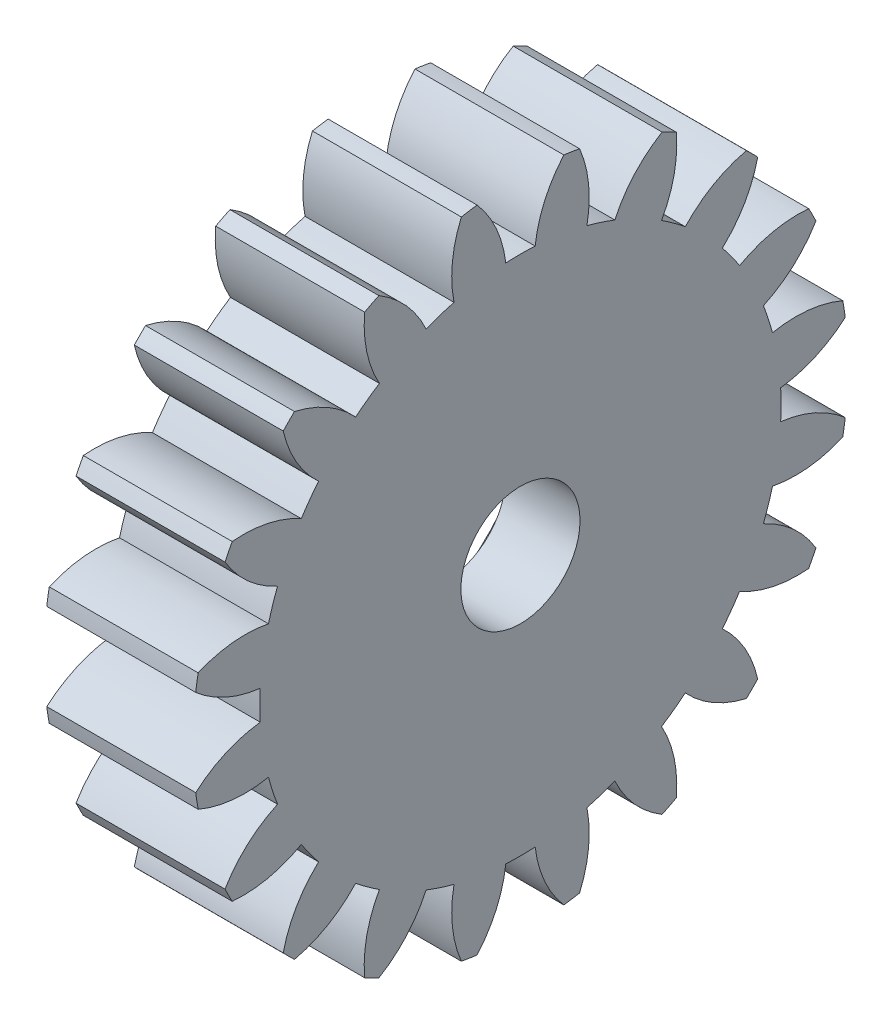
SolidWorks part; units mm, degrees
ref_plane "Front Plane" through (0, 0, 0) normal (0, 0, 1) x (1, 0, 0)
ref_plane "Top Plane" through (0, 0, 0) normal (0, 1, 0) x (1, 0, 0)
ref_plane "Right Plane" through (0, 0, 0) normal (1, 0, 0) x (0, 0, -1)
ref_plane "Plane1" through (-18.1667, 0, 0) normal (1, 0, 0) x (0, 0, -1)
sketch "Sketch1" plane through (-18.1667, 0, 0) normal (1, 0, 0) x (0, 0, -1)
  circle A0 centre (-10.2644, 2.8855) radius 11
  arc A1 (-32.0707, 5.7982) -> (-27.7356, 3.8717) centre (-26.8004, 11.8169) ccw
  arc A2 (-27.7356, 3.8717) -> (-27.7356, 1.8994) centre (-10.2644, 2.8855) ccw
  arc A3 (-27.7356, 1.8994) -> (-32.0707, -0.0272) centre (-26.8004, -6.0458) ccw
  arc A4 (-32.0707, -0.0272) -> (-31.9035, -1.0829) centre (-10.2644, 2.8855) ccw
  arc A5 (-31.9035, -1.0829) -> (-27.1852, -1.5755) centre (-28.751, 6.2698) ccw
  arc A6 (-27.1852, -1.5755) -> (-26.5757, -3.4513) centre (-10.2644, 2.8855) ccw
  arc A7 (-26.5757, -3.4513) -> (-30.1033, -6.6231) centre (-23.2311, -10.7186) ccw
  arc A8 (-30.1033, -6.6231) -> (-29.6181, -7.5755) centre (-10.2644, 2.8855) ccw
  arc A9 (-29.6181, -7.5755) -> (-24.9785, -6.586) centre (-28.892, 0.3915) ccw
  arc A10 (-24.9785, -6.586) -> (-23.8192, -8.1816) centre (-10.2644, 2.8855) ccw
  arc A11 (-23.8192, -8.1816) -> (-26.194, -12.2883) centre (-18.3926, -14.0597) ccw
  arc A12 (-26.194, -12.2883) -> (-25.4382, -13.0441) centre (-10.2644, 2.8855) ccw
  arc A13 (-25.4382, -13.0441) -> (-21.3315, -10.6693) centre (-27.2096, -5.2427) ccw
  arc A14 (-21.3315, -10.6693) -> (-19.7358, -11.8286) centre (-10.2644, 2.8855) ccw
  arc A15 (-19.7358, -11.8286) -> (-20.7254, -16.4682) centre (-12.7584, -15.7421) ccw
  arc A16 (-20.7254, -16.4682) -> (-19.773, -16.9535) centre (-10.2644, 2.8855) ccw
  arc A17 (-19.773, -16.9535) -> (-16.6012, -13.4258) centre (-23.8685, -10.0812) ccw
  arc A18 (-16.6012, -13.4258) -> (-14.7254, -14.0353) centre (-10.2644, 2.8855) ccw
  arc A19 (-14.7254, -14.0353) -> (-14.2328, -18.7536) centre (-6.8801, -15.6011) ccw
  arc A20 (-14.2328, -18.7536) -> (-13.1771, -18.9208) centre (-10.2644, 2.8855) ccw
  arc A21 (-13.1771, -18.9208) -> (-11.2505, -14.5857) centre (-19.1957, -13.6505) ccw
  arc A22 (-11.2505, -14.5857) -> (-9.2782, -14.5857) centre (-10.2644, 2.8855) ccw
  arc A23 (-9.2782, -14.5857) -> (-7.3517, -18.9208) centre (-1.333, -13.6505) ccw
  arc A24 (-7.3517, -18.9208) -> (-6.296, -18.7536) centre (-10.2644, 2.8855) ccw
  arc A25 (-6.296, -18.7536) -> (-5.8034, -14.0353) centre (-13.6486, -15.6011) ccw
  arc A26 (-5.8034, -14.0353) -> (-3.9276, -13.4258) centre (-10.2644, 2.8855) ccw
  arc A27 (-3.9276, -13.4258) -> (-0.7557, -16.9535) centre (3.3397, -10.0812) ccw
  arc A28 (-0.7557, -16.9535) -> (0.1967, -16.4682) centre (-10.2644, 2.8855) ccw
  arc A29 (0.1967, -16.4682) -> (-0.7929, -11.8286) centre (-7.7703, -15.7421) ccw
  arc A30 (-0.7929, -11.8286) -> (0.8028, -10.6693) centre (-10.2644, 2.8855) ccw
  arc A31 (0.8028, -10.6693) -> (4.9095, -13.0441) centre (6.6809, -5.2427) ccw
  arc A32 (4.9095, -13.0441) -> (5.6653, -12.2883) centre (-10.2644, 2.8855) ccw
  arc A33 (5.6653, -12.2883) -> (3.2905, -8.1816) centre (-2.1361, -14.0597) ccw
  arc A34 (3.2905, -8.1816) -> (4.4498, -6.586) centre (-10.2644, 2.8855) ccw
  arc A35 (4.4498, -6.586) -> (9.0894, -7.5755) centre (8.3633, 0.3915) ccw
  arc A36 (9.0894, -7.5755) -> (9.5746, -6.6231) centre (-10.2644, 2.8855) ccw
  arc A37 (9.5746, -6.6231) -> (6.047, -3.4513) centre (2.7024, -10.7186) ccw
  arc A38 (6.047, -3.4513) -> (6.6565, -1.5755) centre (-10.2644, 2.8855) ccw
  arc A39 (6.6565, -1.5755) -> (11.3748, -1.0829) centre (8.2223, 6.2698) ccw
  arc A40 (11.3748, -1.0829) -> (11.542, -0.0272) centre (-10.2644, 2.8855) ccw
  arc A41 (11.542, -0.0272) -> (7.2068, 1.8994) centre (6.2717, -6.0458) ccw
  arc A42 (7.2068, 1.8994) -> (7.2068, 3.8717) centre (-10.2644, 2.8855) ccw
  arc A43 (7.2068, 3.8717) -> (11.542, 5.7982) centre (6.2717, 11.8169) ccw
  arc A44 (11.542, 5.7982) -> (11.3748, 6.8539) centre (-10.2644, 2.8855) ccw
  arc A45 (11.3748, 6.8539) -> (6.6565, 7.3465) centre (8.2223, -0.4988) ccw
  arc A46 (6.6565, 7.3465) -> (6.047, 9.2223) centre (-10.2644, 2.8855) ccw
  arc A47 (6.047, 9.2223) -> (9.5746, 12.3942) centre (2.7024, 16.4896) ccw
  arc A48 (9.5746, 12.3942) -> (9.0894, 13.3465) centre (-10.2644, 2.8855) ccw
  arc A49 (9.0894, 13.3465) -> (4.4498, 12.357) centre (8.3633, 5.3796) ccw
  arc A50 (4.4498, 12.357) -> (3.2905, 13.9527) centre (-10.2644, 2.8855) ccw
  arc A51 (3.2905, 13.9527) -> (5.6653, 18.0594) centre (-2.1361, 19.8308) ccw
  arc A52 (5.6653, 18.0594) -> (4.9095, 18.8152) centre (-10.2644, 2.8855) ccw
  arc A53 (4.9095, 18.8152) -> (0.8028, 16.4404) centre (6.6809, 11.0138) ccw
  arc A54 (0.8028, 16.4404) -> (-0.7929, 17.5997) centre (-10.2644, 2.8855) ccw
  arc A55 (-0.7929, 17.5997) -> (0.1967, 22.2393) centre (-7.7703, 21.5132) ccw
  arc A56 (0.1967, 22.2393) -> (-0.7557, 22.7245) centre (-10.2644, 2.8855) ccw
  arc A57 (-0.7557, 22.7245) -> (-3.9276, 19.1969) centre (3.3397, 15.8523) ccw
  arc A58 (-3.9276, 19.1969) -> (-5.8034, 19.8064) centre (-10.2644, 2.8855) ccw
  arc A59 (-5.8034, 19.8064) -> (-6.296, 24.5247) centre (-13.6486, 21.3722) ccw
  arc A60 (-6.296, 24.5247) -> (-7.3517, 24.6919) centre (-10.2644, 2.8855) ccw
  arc A61 (-7.3517, 24.6919) -> (-9.2782, 20.3567) centre (-1.333, 19.4216) ccw
  arc A62 (-9.2782, 20.3567) -> (-11.2505, 20.3567) centre (-10.2644, 2.8855) ccw
  arc A63 (-11.2505, 20.3567) -> (-13.1771, 24.6919) centre (-19.1957, 19.4216) ccw
  arc A64 (-13.1771, 24.6919) -> (-14.2328, 24.5247) centre (-10.2644, 2.8855) ccw
  arc A65 (-14.2328, 24.5247) -> (-14.7254, 19.8064) centre (-6.8801, 21.3722) ccw
  arc A66 (-14.7254, 19.8064) -> (-16.6012, 19.1969) centre (-10.2644, 2.8855) ccw
  arc A67 (-16.6012, 19.1969) -> (-19.773, 22.7245) centre (-23.8685, 15.8523) ccw
  arc A68 (-19.773, 22.7245) -> (-20.7254, 22.2393) centre (-10.2644, 2.8855) ccw
  arc A69 (-20.7254, 22.2393) -> (-19.7358, 17.5997) centre (-12.7584, 21.5132) ccw
  arc A70 (-19.7358, 17.5997) -> (-21.3315, 16.4404) centre (-10.2644, 2.8855) ccw
  arc A71 (-21.3315, 16.4404) -> (-25.4382, 18.8152) centre (-27.2096, 11.0138) ccw
  arc A72 (-25.4382, 18.8152) -> (-26.194, 18.0594) centre (-10.2644, 2.8855) ccw
  arc A73 (-26.194, 18.0594) -> (-23.8192, 13.9527) centre (-18.3926, 19.8308) ccw
  arc A74 (-23.8192, 13.9527) -> (-24.9785, 12.357) centre (-10.2644, 2.8855) ccw
  arc A75 (-24.9785, 12.357) -> (-29.6181, 13.3465) centre (-28.892, 5.3796) ccw
  arc A76 (-29.6181, 13.3465) -> (-30.1033, 12.3942) centre (-10.2644, 2.8855) ccw
  arc A77 (-30.1033, 12.3942) -> (-26.5757, 9.2223) centre (-23.2311, 16.4896) ccw
  arc A78 (-26.5757, 9.2223) -> (-27.1852, 7.3465) centre (-10.2644, 2.8855) ccw
  arc A79 (-27.1852, 7.3465) -> (-31.9035, 6.8539) centre (-28.751, -0.4988) ccw
  arc A80 (-31.9035, 6.8539) -> (-32.0707, 5.7982) centre (-10.2644, 2.8855) ccw
extrude "Boss-Extrude1" add sketch "Sketch1" against normal blind 10
sketch "Sketch2" plane through (-18.1667, 0, 0) normal (1, 0, 0) x (0, 0, -1)
  circle A0 centre (-10.2644, 2.8855) radius 11
  dimension "D1" = 22
extrude "Boss-Extrude2" add sketch "Sketch2" against normal blind 5
sketch "Sketch3" plane through (-18.1667, 0, 0) normal (1, 0, 0) x (0, 0, -1)
  circle A0 centre (-10.2644, 2.8855) radius 4
  dimension "D1" = 8
extrude "Cut-Extrude1" cut sketch "Sketch3" against normal blind 5
